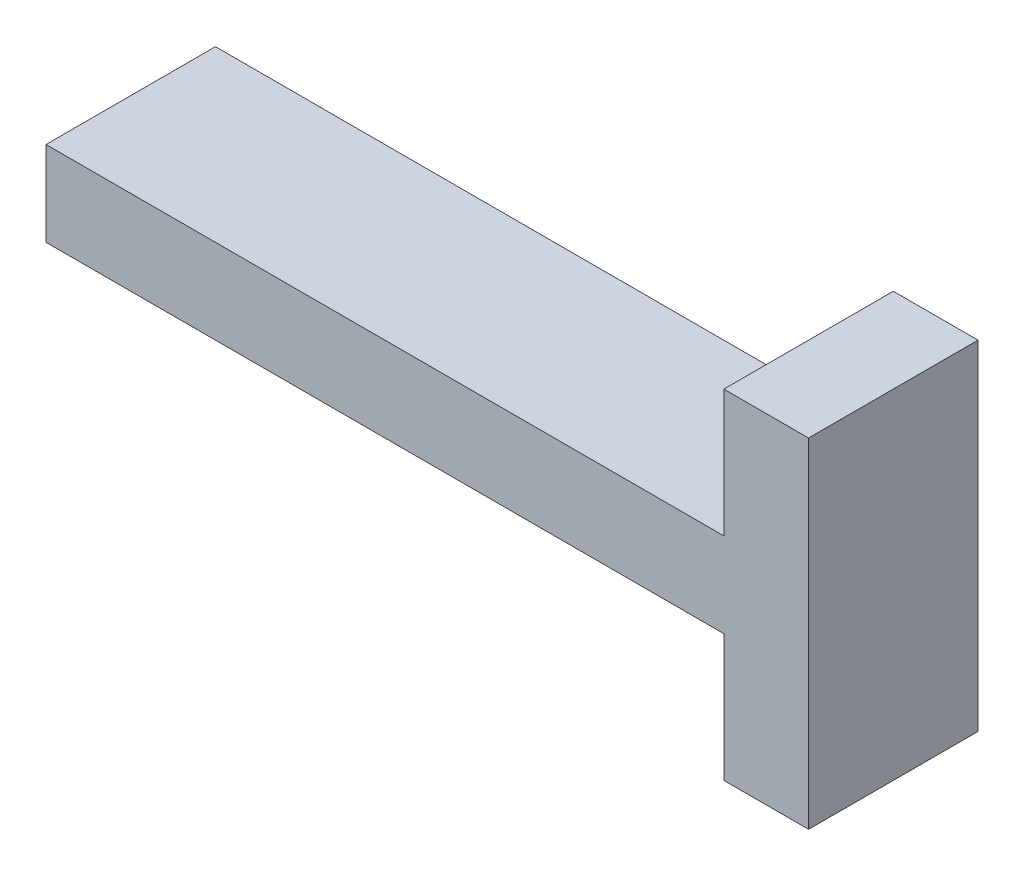
SolidWorks part; units mm, degrees
ref_plane "Front Plane" through (0, 0, 0) normal (0, 0, 1) x (1, 0, 0)
ref_plane "Top Plane" through (0, 0, 0) normal (0, 1, 0) x (1, 0, 0)
ref_plane "Right Plane" through (0, 0, 0) normal (1, 0, 0) x (0, 0, -1)
sketch "Sketch1" plane through (0, 0, 0) normal (0, 0, 1) x (1, 0, 0)
  line L0 (0, 0) -> (0, 15)
  line L1 (0, 15) -> (10, 15)
  line L2 (10, 15) -> (10, -25)
  line L3 (10, -25) -> (0, -25)
  line L4 (0, -25) -> (0, -10)
  line L5 (0, -10) -> (-80, -10)
  line L6 (-80, -10) -> (-80, 0)
  line L7 (-80, 0) -> (0, 0)
  dimension "D1" = 40
  dimension "D2" = 10
  dimension "D3" = 80
  dimension "D4" = 10
  dimension "D5" = 15
extrude "Boss-Extrude1" add sketch "Sketch1" along normal blind 20
